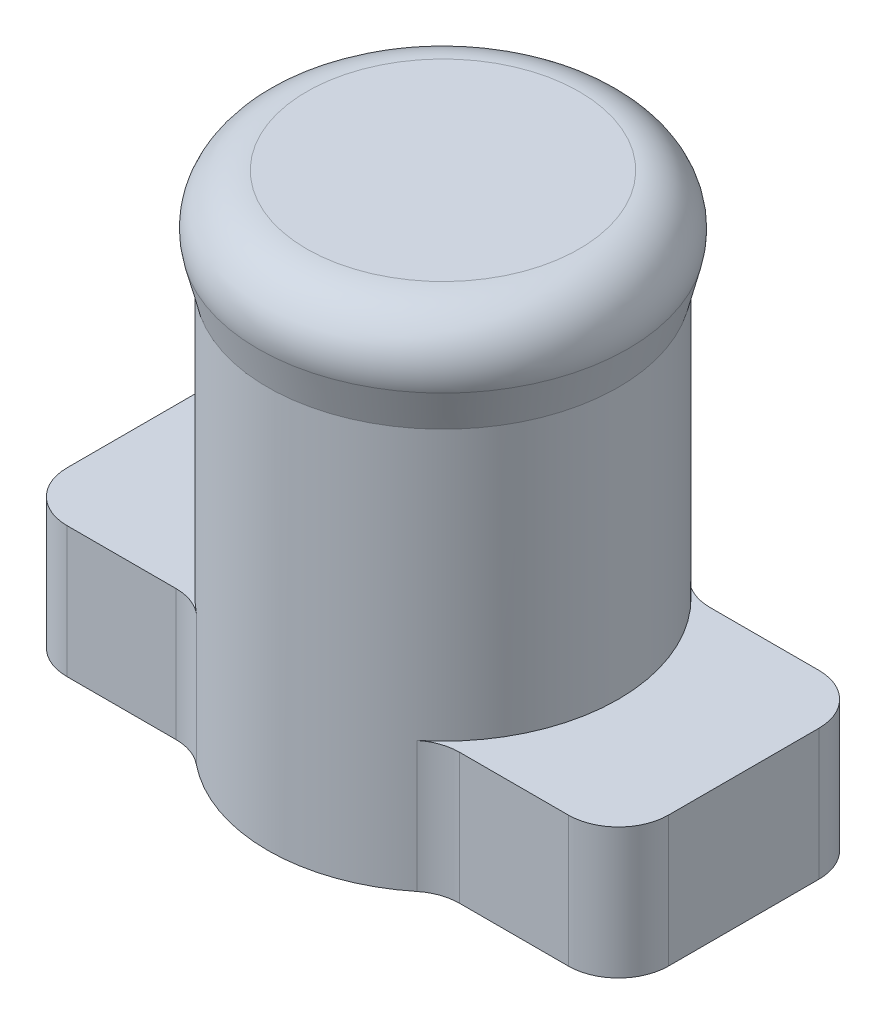
SolidWorks part; units mm, degrees
ref_plane "Front Plane" through (0, 0, 0) normal (0, 0, 1) x (1, 0, 0)
ref_plane "Top Plane" through (0, 0, 0) normal (0, 1, 0) x (1, 0, 0)
ref_plane "Right Plane" through (0, 0, 0) normal (1, 0, 0) x (0, 0, -1)
sketch "Sketch1" plane through (0, 0, 0) normal (0, 0, 1) x (1, 0, 0)
  line L0 (0, 0) -> (0, 10)
  line L1 (0, 10) -> (4, 10)
  line L5 (3.5, 0) -> (0, 0)
  line L8 (3.5, 0) -> (3.5, 8)
  line L9 (3.5, 8) -> (4, 10)
  dimension "D1" = 4
  dimension "D2" = 10
  dimension "D3" = 3.5
  dimension "D4" = 8
revolve "Revolve1" add sketch "Sketch1" angle 360 about L0
sketch "Sketch3" plane through (0, 0, 0) normal (0, -1, 0) x (1, 0, 0)
  line L1 (-1.8, -1.8) -> (1.8, -1.8)
  line L2 (-1.8, -1.8) -> (-1.8, 1.8)
  line L3 (-1.8, 1.8) -> (1.8, 1.8)
  line L4 (1.8, -1.8) -> (1.8, 1.8)
  line L5 (-1.8, -1.8) -> (1.8, 1.8) construction
  line L6 (-1.8, 1.8) -> (1.8, -1.8) construction
  point P0 (0, 0)
  dimension "D2" = 3.6
extrude "Cut-Extrude2" cut sketch "Sketch3" against normal blind 3.5
sketch "Sketch4" plane through (0, 0, 0) normal (0, 1, 0) x (1, 0, 0)
  line L0 (-3.9, 0) -> (0, 0) construction
  line L1 (-1.8, 2.5) -> (-6, 2.5)
  line L2 (-1.8, 2.5) -> (-1.8, -2.5)
  line L3 (-1.8, -2.5) -> (-6, -2.5)
  line L4 (-6, 2.5) -> (-6, -2.5)
  line L5 (-1.8, 2.5) -> (-6, -2.5) construction
  line L6 (-1.8, -2.5) -> (-6, 2.5) construction
  line L7 (6, -2.5) -> (1.8, -2.5)
  line L8 (6, -2.5) -> (6, 2.5)
  line L9 (6, 2.5) -> (1.8, 2.5)
  line L10 (1.8, -2.5) -> (1.8, 2.5)
  line L11 (6, -2.5) -> (1.8, 2.5) construction
  line L12 (6, 2.5) -> (1.8, -2.5) construction
  line L13 (0, 0) -> (3.9, 0) construction
  line L14 (-1.8, -1.8) -> (-1.8, 1.8) construction
  line L15 (-3.5, 3.4123) -> (-3.5, -3.7854) construction
  circle A0 centre (0, 0) radius 3.5 construction
  point P0 (-3.9, 0)
  point P6 (3.9, 0)
  dimension "D1" = 5
  dimension "D2" = 2.5
extrude "Boss-Extrude1" add sketch "Sketch4" along normal up to vertex (2.61 mm away)
fillet "Fillet1" radius 1 9 edges at (2.4495, 1.305, 2.5) (6, 1.305, 2.5) (6, 1.305, -2.5) (2.4495, 1.305, -2.5) (-2.4495, 1.305, -2.5) (-6, 1.305, -2.5) (-6, 1.305, 2.5) (-2.4495, 1.305, 2.5) (0, 10, -4)
